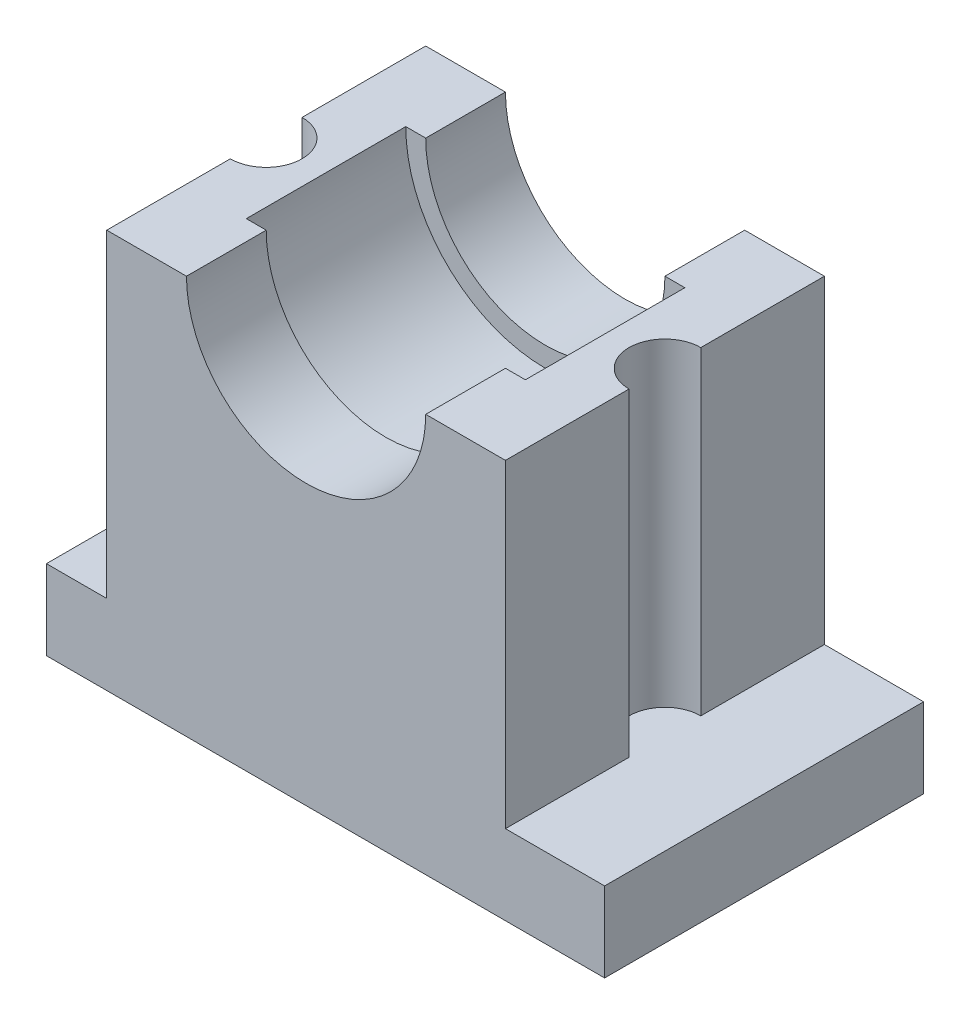
SolidWorks part; units mm, degrees
ref_plane "Front Plane" through (0, 0, 0) normal (0, 0, 1) x (1, 0, 0)
ref_plane "Top Plane" through (0, 0, 0) normal (0, 1, 0) x (1, 0, 0)
ref_plane "Right Plane" through (0, 0, 0) normal (1, 0, 0) x (0, 0, -1)
sketch "Sketch1" plane through (0, 0, 0) normal (0, 0, 1) x (1, 0, 0)
  line L0 (-99.0177, -13.5363) -> (40.9823, -13.5363)
  line L1 (40.9823, -13.5363) -> (40.9823, 6.4637)
  line L2 (40.9823, 6.4637) -> (16.11, 6.4637)
  line L3 (16.11, 6.4637) -> (16.11, 86.4637)
  line L4 (16.11, 86.4637) -> (-3.89, 86.4637)
  line L5 (-99.0177, -13.5363) -> (-99.0177, 6.4637)
  line L6 (-99.0177, 6.4637) -> (-83.89, 6.4637)
  line L7 (-83.89, 6.4637) -> (-83.89, 86.4637)
  line L8 (-83.89, 86.4637) -> (-63.89, 86.4637)
  circle A0 centre (-33.89, 86.4637) radius 30
  point P12 (0, 0)
  dimension "D1" = 140
  dimension "D2" = 20
  dimension "D3" = 20
  dimension "D4" = 100
  dimension "D5" = 80
  dimension "D6" = 80
  dimension "D7" = 20
  dimension "D8" = 20
extrude "Boss-Extrude1" add sketch "Sketch1" against normal blind 80 contours A0 L8 L7 L6 L5 L0 L1 L2 L3 L4
sketch "Sketch2" plane through (0, 86.4637, 0) normal (0, 1, 0) x (1, 0, 0)
  line L0 (16.11, 80) -> (16.11, 0) construction
  line L1 (-83.89, 80) -> (-83.89, 0) construction
  circle A0 centre (16.11, 40) radius 9
  circle A1 centre (-83.89, 40) radius 9
extrude "Cut-Extrude1" cut sketch "Sketch2" against normal blind 80
move or copy body "Body-Move/Copy1" bodies to move or copy 102 copy no translate (0, 0, 20) parameters "D1"=0, "D2"=0, "D3"=20
sketch "Sketch5" plane through (0, 0, 0) normal (0, 0, 1) x (1, 0, 0)
  circle A0 centre (-33.89, 86.4637) radius 35
extrude "Cut-Extrude2" cut sketch "Sketch5" against normal blind 40
